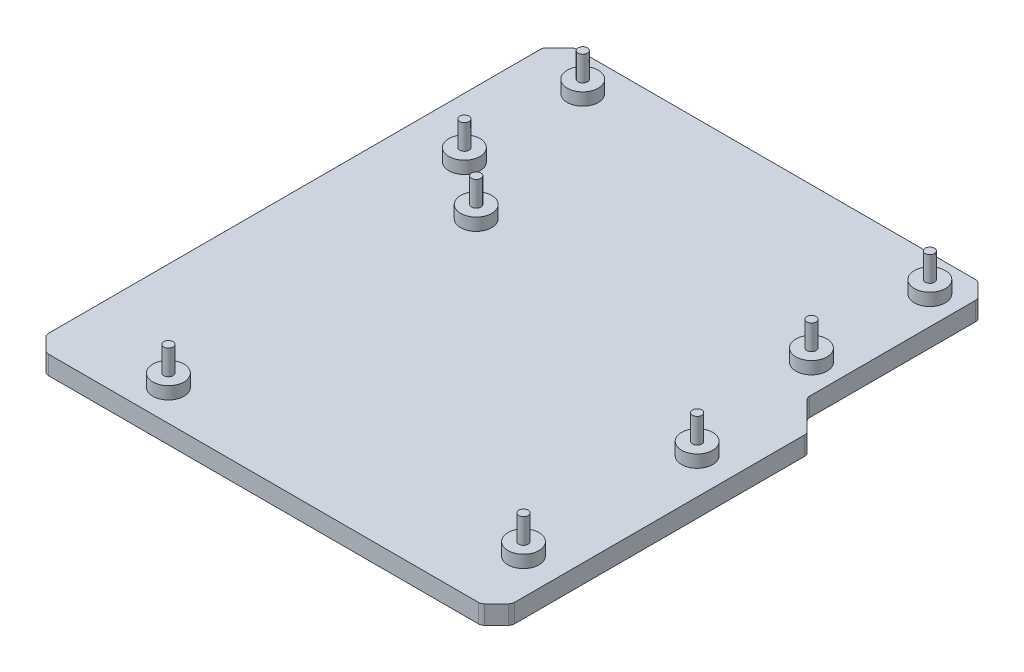
SolidWorks part; units mm, degrees
ref_plane "Front Plane" through (0, 0, 0) normal (0, 0, 1) x (1, 0, 0)
ref_plane "Top Plane" through (0, 0, 0) normal (0, 1, 0) x (1, 0, 0)
ref_plane "Right Plane" through (0, 0, 0) normal (1, 0, 0) x (0, 0, -1)
sketch "Sketch1" plane through (0, 0, 0) normal (0, 1, 0) x (1, 0, 0)
  line L1 (-37.5, 42.5) -> (37.5, 42.5)
  line L2 (-37.5, 42.5) -> (-37.5, -42.5)
  line L3 (-37.5, -42.5) -> (37.5, -42.5)
  line L4 (37.5, 42.5) -> (37.5, -42.5)
  line L5 (-37.5, 42.5) -> (37.5, -42.5) construction
  line L6 (-37.5, -42.5) -> (37.5, 42.5) construction
  point P0 (0, 0)
  dimension "D1" = 85
  dimension "D2" = 75
extrude "Boss-Extrude1" add sketch "Sketch1" along normal blind 3
sketch "Sketch2" plane through (0, 3, 0) normal (0, 1, 0) x (1, 0, 0)
  line L0 (37.5, 42.5) -> (27.93, 42.5) construction
  line L1 (0, -1.65) -> (0, 1.65) construction
  line L2 (-37.5, 42.5) -> (-37.5, -42.5) construction
  line L3 (37.5, 42.5) -> (-37.5, 42.5) construction
  line L4 (27.93, 42.5) -> (27.93, 36.82) construction
  line L5 (37.5, -42.5) -> (37.5, 42.5) construction
  circle A0 centre (27.93, 36.82) radius 2.5
  circle A1 centre (27.93, 17.77) radius 2.5
  circle A3 centre (-27.93, 17.77) radius 2.5
  circle A4 centre (-27.93, 36.82) radius 2.5
  circle A5 centre (-19.05, 10.79) radius 2.5
  circle A6 centre (-20.32, -37.48) radius 2.5
  circle A7 centre (31.75, -4.45) radius 2.5
  circle A8 centre (31.75, -32.4) radius 2.5
  dimension "D3" = 5
  dimension "D5" = 5
  dimension "D7" = 5
  dimension "D10" = 5
  dimension "D13" = 5
  dimension "D16" = 5
  dimension "D1" = 9.57
  dimension "D4" = 19.05
  dimension "D2" = 5.68
  dimension "D6" = 18.45
  dimension "D8" = 6.98
  dimension "D9" = 48.27
  dimension "D11" = 17.18
  dimension "D12" = 5.75
  dimension "D14" = 22.22
  dimension "D15" = 27.95
  dimension "D17" = 5.75
extrude "Boss-Extrude2" add sketch "Sketch2" along normal blind 2
sketch "Sketch3" plane through (0, 5, 0) normal (0, 1, 0) x (1, 0, 0)
  line L0 (0, -2.75) -> (0, 2.75) construction
  line L1 (-27.93, 36.82) -> (-27.93, 17.77) construction
  line L2 (-27.93, 27.295) -> (-10.539, 27.295) construction
  circle A0 centre (-27.93, 36.82) radius 0.75
  circle A1 centre (27.93, 36.82) radius 0.75
  circle A2 centre (27.93, 17.77) radius 0.75
  circle A3 centre (-27.93, 17.77) radius 0.75
  circle A4 centre (-19.05, 10.79) radius 0.75
  circle A5 centre (31.75, -4.45) radius 0.75
  circle A6 centre (-20.32, -37.48) radius 0.75
  circle A7 centre (31.75, -32.4) radius 0.75
  dimension "D1" = 1.5
  dimension "D2" = 1.5
extrude "Boss-Extrude3" add sketch "Sketch3" along normal blind 4
sketch "Sketch4" plane through (0, 3, 0) normal (0, 1, 0) x (1, 0, 0)
  line L0 (37.5, -42.5) -> (37.5, 7.5) construction
  line L1 (37.5, -42.5) -> (37.5, 42.5) construction
  line L7 (37.5, 7.5) -> (32.5, 12.5)
  line L8 (32.5, 12.5) -> (32.5, 42.5)
  line L10 (37.5, 42.5) -> (-37.5, 42.5) construction
  line L11 (32.5, 42.5) -> (37.5, 42.5)
  line L12 (37.5, 42.5) -> (37.5, 7.5)
  dimension "D1" = 50
  dimension "D2" = 45
  dimension "D3" = 5
extrude "Cut-Extrude1" cut sketch "Sketch4" against normal up to next
chamfer "Chamfer3" distance 2.5 angle 45 4 edges at (-37.5, 1.5, 42.5) (-37.5, 1.5, -42.5) (37.5, 1.5, 42.5) (32.5, 1.5, -42.5)
fillet "Fillet2" radius 1 10 edges at (-37.5, 1.5, -40) (-35, 1.5, -42.5) (30, 1.5, -42.5) (32.5, 1.5, -40) (32.5, 1.5, -12.5) (37.5, 1.5, -7.5) (37.5, 1.5, 40) (35, 1.5, 42.5) (-37.5, 1.5, 40) (-35, 1.5, 42.5)
sketch "Sketch5" plane through (0, 0, 0) normal (0, -1, 0) x (1, 0, 0)
  line L1 (14.925, -10.9875) -> (5.075, -10.9875)
  line L2 (14.925, -10.9875) -> (14.925, -7.1375)
  line L3 (14.925, -7.1375) -> (5.075, -7.1375)
  line L4 (5.075, -10.9875) -> (5.075, -7.1375)
  line L5 (14.925, -10.9875) -> (5.075, -7.1375) construction
  line L6 (14.925, -7.1375) -> (5.075, -10.9875) construction
  line L8 (29.5858, -42.5) -> (-34.5858, -42.5) construction
  line L9 (0, -4.95) -> (0, 4.95) construction
  line L10 (-14.925, -7.1375) -> (-5.075, -7.1375)
  line L11 (-5.075, -10.9875) -> (-5.075, -7.1375)
  line L12 (-14.925, -10.9875) -> (-5.075, -10.9875)
  line L13 (-14.925, -10.9875) -> (-14.925, -7.1375)
  point P4 (10, -9.0625)
  dimension "D1" = 33.4375
  dimension "D2" = 10
  dimension "D3" = 3.85
  dimension "D4" = 9.85
extrude "Boss-Extrude4" add sketch "Sketch5" along normal blind 3
fillet "Fillet3" radius 2 4 edges at (-10, 0, -10.9875) (-10, 0, -7.1375) (10, 0, -7.1375) (10, 0, -10.9875)
sketch "Sketch6" plane through (-14.925, 0, 0) normal (-1, 0, 0) x (0, 0, 1)
  line L0 (41.25, 0) -> (-41.25, 0) construction
  line L1 (-9.8875, 0) -> (-8.3875, 0)
  line L2 (-9.8875, 0) -> (-9.8875, -3)
  line L3 (-9.8875, -3) -> (-8.3875, -3)
  line L4 (-8.3875, 0) -> (-8.3875, -3)
  line L5 (-9.8875, 0) -> (-8.3875, -3) construction
  line L6 (-9.8875, -3) -> (-8.3875, 0) construction
  line L7 (-7.1375, -3) -> (-10.9875, -3) construction
  line L8 (-7.1375, -3) -> (-7.1375, -2) construction
  point P4 (-9.1375, -1.5)
  point P7 (-8.5572, -3)
  point P10 (-8.4884, -3)
  dimension "D1" = 2
  dimension "D2" = 1.5
extrude "Cut-Extrude2" cut sketch "Sketch6" against normal through all
equation "\"D1@Sketch2\"=1.93+6.39+1.25"
equation "\"D4@Sketch2\"=16.55+2.5"
equation "\"D2@Sketch2\"=1.93+1.25+2.5"
equation "\"D6@Sketch2\"=3.21+13.65+1.59"
equation "\"D8@Sketch2\"=1.26+0.95+1.93+1.25+1.59"
equation "\"D11@Sketch2\"=12.38+3.21+1.59"
equation "\"D9@Sketch2\"=45.09+2*1.59"
equation "\"D12@Sketch2\"=0.95+1.59+3.21"
equation "\"D14@Sketch2\"=17.45+1.59+1.25+1.93mm"
equation "\"D15@Sketch2\"=24.77+2*1.59"
equation "\"D17@Sketch2\"=0.95+1.59+3.21"
